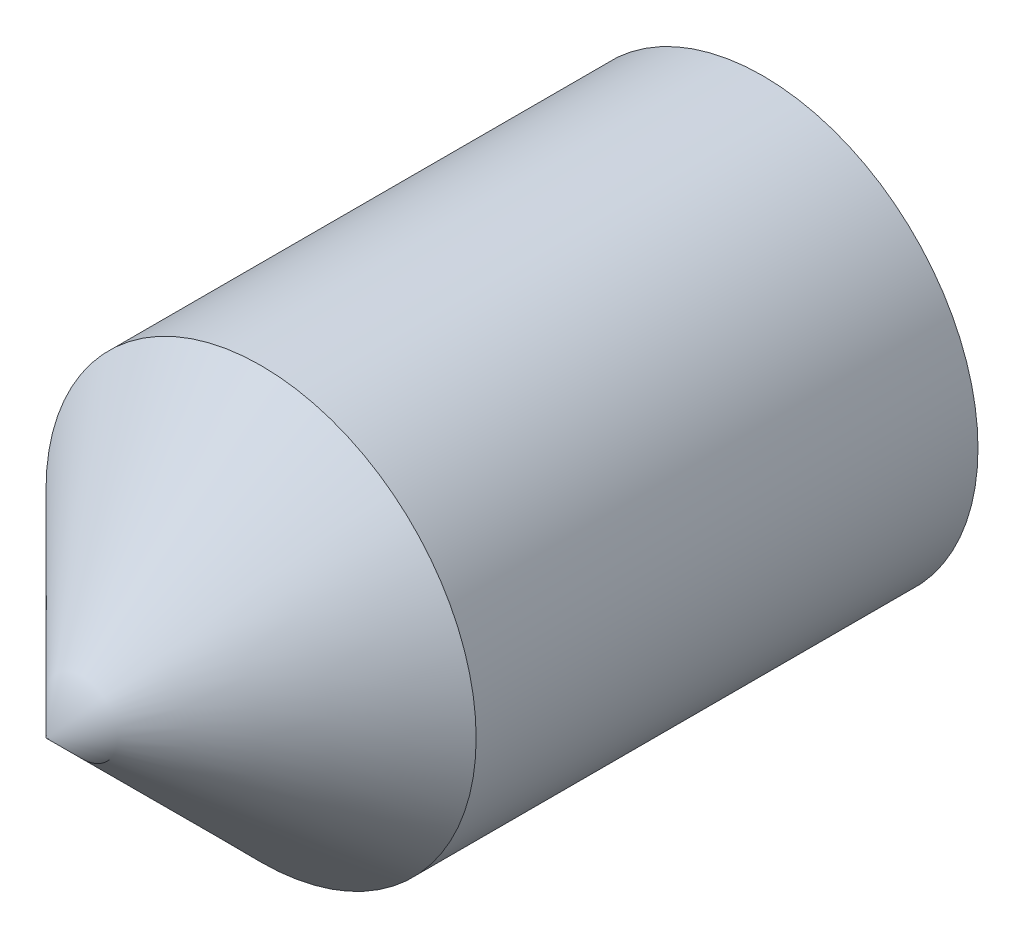
SolidWorks part; units mm, degrees
ref_plane "Front Plane" through (0, 0, 0) normal (0, 0, 1) x (1, 0, 0)
ref_plane "Top Plane" through (0, 0, 0) normal (0, 1, 0) x (1, 0, 0)
ref_plane "Right Plane" through (0, 0, 0) normal (1, 0, 0) x (0, 0, -1)
sketch "Sketch1" plane through (0, 0, 0) normal (0, 0, 1) x (1, 0, 0)
  circle A0 centre (0, 0) radius 7.5
  dimension "15mm" = 15
extrude "Boss-Extrude1" add sketch "Sketch1" along normal blind 25
chamfer "Chamfer1" distance 7.5 angle 45 1 edges at (7.5, 0, 25)
